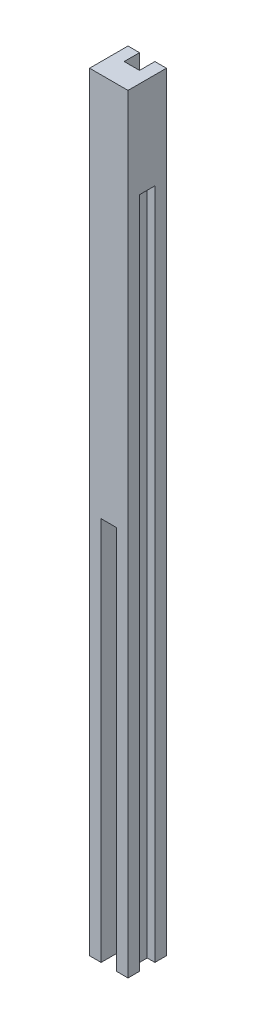
SolidWorks part; units mm, degrees
ref_plane "Front Plane" through (0, 0, 0) normal (0, 0, 1) x (1, 0, 0)
ref_plane "Top Plane" through (0, 0, 0) normal (0, 1, 0) x (1, 0, 0)
ref_plane "Right Plane" through (0, 0, 0) normal (1, 0, 0) x (0, 0, -1)
sketch "Sketch1" plane through (0, 0, 0) normal (0, 1, 0) x (1, 0, 0)
  line L1 (-43.4919, 32.6944) -> (-33.4919, 32.6944)
  line L2 (-43.4919, 32.6944) -> (-43.4919, 22.6944)
  line L3 (-43.4919, 22.6944) -> (-33.4919, 22.6944)
  line L4 (-33.4919, 32.6944) -> (-33.4919, 22.6944)
  dimension "D2" = 10
extrude "Boss-Extrude1" add sketch "Sketch1" along normal blind 200
sketch "Sketch2" plane through (0, 0, -22.6944) normal (0, 0, 1) x (1, 0, 0)
  line L0 (-43.4919, 200) -> (-43.4919, 0) construction
  line L1 (-40.4919, 100) -> (-36.4919, 100)
  line L2 (-40.4919, 100) -> (-40.4919, 0)
  line L3 (-40.4919, 0) -> (-36.4919, 0)
  line L4 (-36.4919, 100) -> (-36.4919, 0)
  line L5 (-43.4919, 0) -> (-33.4919, 0) construction
  dimension "D1" = 100
  dimension "D2" = 4
  dimension "D3" = 3
  dimension "D4" = 0
sketch "Sketch3" plane through (0, 0, -32.6944) normal (0, 0, -1) x (-1, 0, 0)
  line L0 (33.4919, 200) -> (43.4919, 200) construction
  line L1 (36.4919, 200) -> (40.4919, 200)
  line L2 (36.4919, 200) -> (36.4919, 100)
  line L3 (36.4919, 100) -> (40.4919, 100)
  line L4 (40.4919, 200) -> (40.4919, 100)
  line L5 (33.4919, 200) -> (33.4919, 0) construction
  dimension "D1" = 4
  dimension "D2" = 3
  dimension "D3" = 100
sketch "Sketch4" plane through (-33.4919, 0, 0) normal (1, 0, 0) x (0, 0, -1)
  line L0 (22.6944, 0) -> (32.6944, 0) construction
  line L1 (25.6944, 175) -> (29.6944, 175)
  line L2 (25.6944, 175) -> (25.6944, 0)
  line L3 (25.6944, 0) -> (29.6944, 0)
  line L4 (29.6944, 175) -> (29.6944, 0)
  line L6 (22.6944, 200) -> (22.6944, 0) construction
  dimension "D1" = 4
  dimension "D2" = 0
  dimension "D3" = 175
  dimension "D4" = 3
sketch "Sketch5" plane through (-43.4919, 0, 0) normal (-1, 0, 0) x (0, 0, 1)
  line L0 (-32.6944, 0) -> (-22.6944, 0) construction
  line L1 (-29.6944, 175) -> (-25.6944, 175)
  line L2 (-29.6944, 175) -> (-29.6944, 0)
  line L3 (-29.6944, 0) -> (-25.6944, 0)
  line L4 (-25.6944, 175) -> (-25.6944, 0)
  line L5 (-32.6944, 200) -> (-32.6944, 0) construction
  dimension "D1" = 4
  dimension "D2" = 0
  dimension "D3" = 175
  dimension "D4" = 3
extrude "Cut-Extrude3" cut sketch "Sketch3" against normal blind 4 contours L1 L4 L3 L2
extrude "Cut-Extrude4" cut sketch "Sketch5" against normal blind 2
extrude "Cut-Extrude5" cut sketch "Sketch2" against normal blind 4 contours L1 L4 L3 L2
extrude "Cut-Extrude6" cut sketch "Sketch4" against normal blind 2 contours L4 L3 L2 L1
equation "\"BeamWidth\" = 10"
equation "\"BeamLength\" = 10"
equation "\"BeamHeight\" = 200"
equation "\"D1@Sketch1\"=\"BeamWidth\""
equation "\"D2@Sketch1\"=\"BeamLength\""
equation "\"D1@Boss-Extrude1\"=\"BeamHeight\""
equation "\"LegHeight\" = 100"
equation "\"LegScannerWidth\" = 4"
equation "\"D1@Sketch2\"=\"LegHeight\""
equation "\"D2@Sketch2\"=\"LegScannerWidth\""
equation "\"D3@Sketch2\"=(\"BeamWidth\"-\"LegScannerWidth\")/2"
equation "\"LegScannerDepth\" = 4"
equation "\"D1@Sketch3\"= \"LegScannerWidth\""
equation "\"D2@Sketch3\"=(\"BeamWidth\"-\"LegScannerWidth\")/2"
equation "\"D3@Sketch3\"=\"LegHeight\""
equation "\"SideRailLength\" = 175"
equation "\"D1@Sketch4\"=\"LegScannerWidth\""
equation "\"D3@Sketch4\"=\"SideRailLength\""
equation "\"D1@Sketch5\"=\"LegScannerWidth\""
equation "\"D3@Sketch5\"=\"SideRailLength\""
equation "\"D4@Sketch5\"=(\"BeamLength\"-\"LegScannerWidth\")/2"
equation "\"D4@Sketch4\"=(\"BeamLength\"-\"LegScannerWidth\")/2"
equation "\"BottomScannerDepth\" =2"
equation "\"D1@Cut-Extrude3\"=\"BottomScannerDepth\""
equation "\"D1@Cut-Extrude4\"=\"BottomScannerDepth\""
equation "\"D1@Cut-Extrude5\"=\"LegScannerDepth\""
equation "\"D1@Cut-Extrude6\"=\"BottomScannerDepth\""
